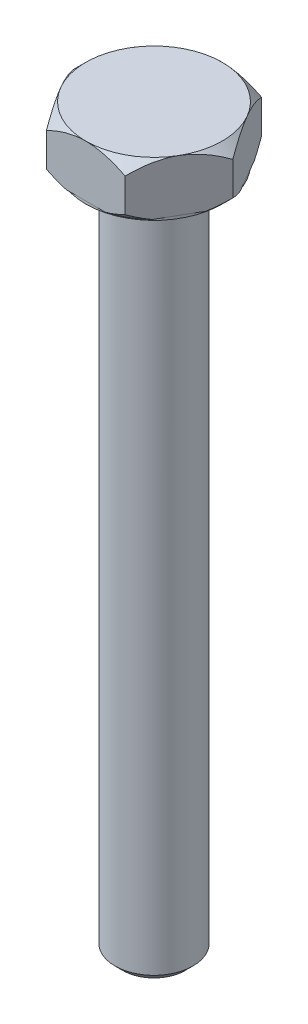
SolidWorks part; units mm, degrees
material "Cast Stainless Steel"
ref_plane "Front Plane" through (0, 0, 0) normal (0, 0, 1) x (1, 0, 0)
ref_plane "Top Plane" through (0, 0, 0) normal (0, 1, 0) x (1, 0, 0)
ref_plane "Right Plane" through (0, 0, 0) normal (1, 0, 0) x (0, 0, -1)
sketch "Sketch1" plane through (0, 0, 0) normal (0, 1, 0) x (1, 0, 0)
  line L0 (0, 0) -> (4.0415, 0) construction
  line L1 (4.0415, 0) -> (2.0207, 3.5)
  line L2 (2.0207, 3.5) -> (-2.0207, 3.5)
  line L3 (-2.0207, 3.5) -> (-4.0415, 0)
  line L4 (-4.0415, 0) -> (-2.0207, -3.5)
  line L5 (-2.0207, -3.5) -> (2.0207, -3.5)
  line L6 (2.0207, -3.5) -> (4.0415, 0)
  circle A0 centre (0, 0) radius 3.5 construction
  dimension "D1" = 7
extrude "Boss-Extrude1" add sketch "Sketch1" against normal blind 2.8
sketch "Sketch4" plane through (0, 0, 0) normal (1, 0, 0) x (0, 0, -1)
  line L0 (-3.5, 0) -> (-4.0415, 0)
  line L1 (-4.0415, 0) -> (-4.0415, -0.5415)
  line L2 (-4.0415, -0.5415) -> (-3.5, 0)
  line L3 (-3.5, -1.4) -> (3.5, -1.4) construction
  line L4 (-4.0415, -2.2585) -> (-3.5, -2.8)
  line L5 (-4.0415, -2.8) -> (-4.0415, -2.2585)
  line L6 (-3.5, -2.8) -> (-4.0415, -2.8)
  line L7 (0, 0) -> (0, -1.4) construction
  dimension "D1" = 45
  dimension "D2" = 1.4
  dimension "D4" = 7
  dimension "D3" = 4.0415
revolve "Cut-Revolve1" cut sketch "Sketch4" angle 360 about L7
sketch "Sketch2" plane through (0, -2.8, 0) normal (0, -1, 0) x (1, 0, 0)
  circle A0 centre (0, 0) radius 3.5
  dimension "D1" = 7
extrude "Cut-Extrude1" cut sketch "Sketch2" against normal blind 0.14 flip side to cut
sketch "Sketch3" plane through (0, -2.8, 0) normal (0, -1, 0) x (1, 0, 0)
  circle A0 centre (0, 0) radius 2
  dimension "D1" = 4
extrude "Boss-Extrude2" add sketch "Sketch3" along normal blind 35
chamfer "Chamfer1" distance 0.4 angle 45 1 edges at (0, -37.8, -2)
equation "\"k\" = 2.8"
equation "\"e\" = 7.66"
equation "\"S\" = 7"
equation "\"L\"= 35"
equation "\"D1@Sketch1\"=\"S\""
equation "\"D1@Boss-Extrude1\"=\"k\""
equation "\"D1@Sketch2\"=\"S\""
equation "\"D1@Cut-Extrude1\"=\"k\"/20"
equation "\"d\"= 4"
equation "\"D1@Sketch3\"=\"d\""
equation "\"D1@Boss-Extrude2\"=\"L\""
equation "\"D2@Sketch4\"=\"k\"/2"
equation "\"D3@Sketch4\"= \"S\" / sqr(3)"
equation "\"D4@Sketch4\"= \"S\""
equation "\"D1@Chamfer1\"=\"d\"/10"
